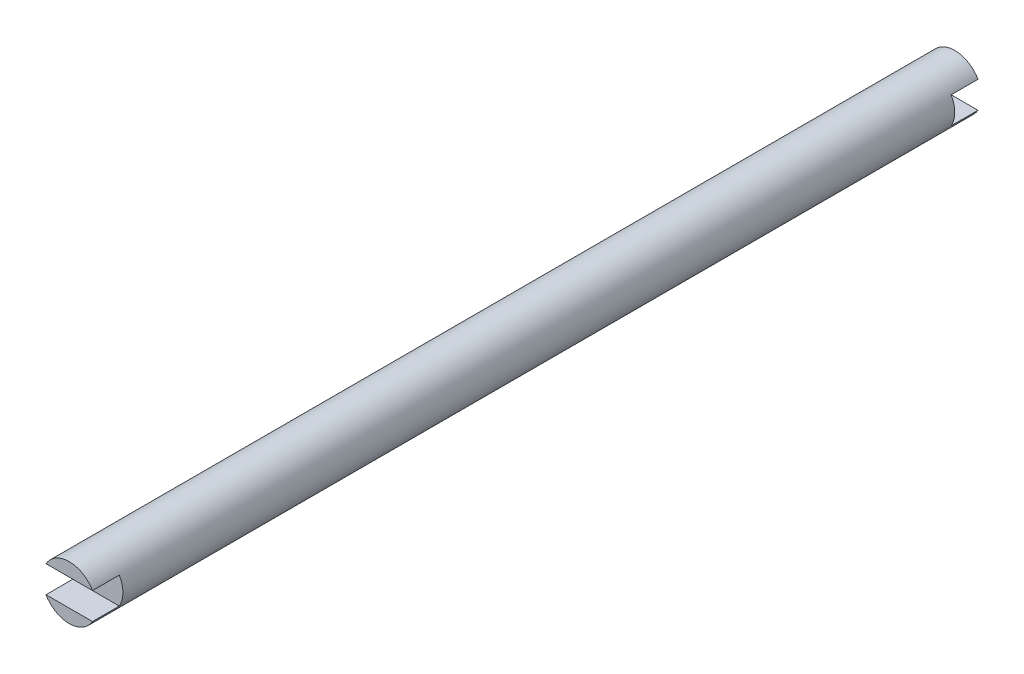
SolidWorks part; units mm, degrees
ref_plane "Plan de face" through (0, 0, 0) normal (0, 0, 1) x (1, 0, 0)
ref_plane "Plan de dessus" through (0, 0, 0) normal (0, 1, 0) x (1, 0, 0)
ref_plane "Plan de droite" through (0, 0, 0) normal (1, 0, 0) x (0, 0, -1)
sketch "Esquisse1" plane through (0, 0, 0) normal (0, 0, 1) x (1, 0, 0)
  circle A0 centre (0, 0) radius 2
  dimension "D1" = 4
extrude "Boss.-Extru.1" add sketch "Esquisse1" along normal blind 66
sketch "Esquisse2" plane through (0, 0, 66) normal (0, 0, 1) x (1, 0, 0)
  line L1 (-3.75, 1) -> (3.75, 1)
  line L2 (-3.75, 1) -> (-3.75, -1)
  line L3 (-3.75, -1) -> (3.75, -1)
  line L4 (3.75, 1) -> (3.75, -1)
  dimension "D1" = 2
  dimension "D2" = 7.5
  dimension "D3" = 3.75
  dimension "D4" = 1
extrude "Enlèv. mat.-Extru.1" cut sketch "Esquisse2" against normal blind 2
sketch "Esquisse3" plane through (0, 0, 0) normal (0, 0, -1) x (-1, 0, 0)
  line L4 (3.75, 1) -> (-3.75, 1)
  line L5 (-3.75, 1) -> (-3.75, -1)
  line L6 (-3.75, -1) -> (3.75, -1)
  line L7 (3.75, -1) -> (3.75, 1)
  line L8 (3.75, 1) -> (-3.75, 1)
  line L9 (-3.75, 1) -> (-3.75, -1)
  line L10 (-3.75, -1) -> (3.75, -1)
  line L11 (3.75, -1) -> (3.75, 1)
  circle A1 centre (0, 0) radius 2
  circle A2 centre (0, 0) radius 2
  dimension "D1" = 0
  dimension "D2" = 0
extrude "Enlèv. mat.-Extru.2" cut sketch "Esquisse3" against normal blind 2 contours L8 L9 L10 L11
